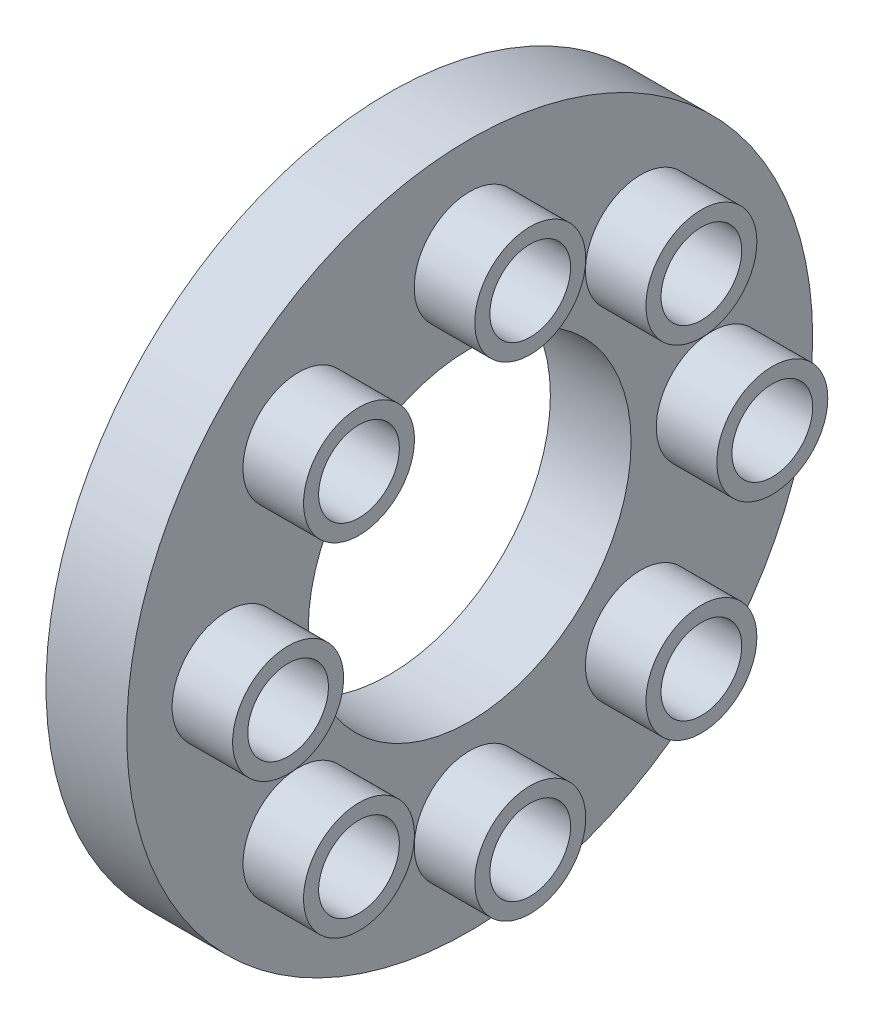
SolidWorks part; units mm, degrees
ref_plane "Front Plane" through (0, 0, 0) normal (0, 0, 1) x (1, 0, 0)
ref_plane "Top Plane" through (0, 0, 0) normal (0, 1, 0) x (1, 0, 0)
ref_plane "Right Plane" through (0, 0, 0) normal (1, 0, 0) x (0, 0, -1)
sketch "Sketch1" plane through (0, 0, 0) normal (1, 0, 0) x (0, 0, -1)
  line L0 (0, 0) -> (0, 12) construction
  circle A0 centre (0, 0) radius 17
  circle A1 centre (0, 12) radius 2
  circle A2 centre (8.4853, 8.4853) radius 2
  circle A3 centre (12, 0) radius 2
  circle A4 centre (8.4853, -8.4853) radius 2
  circle A5 centre (0, -12) radius 2
  circle A6 centre (-8.4853, -8.4853) radius 2
  circle A7 centre (-12, 0) radius 2
  circle A8 centre (-8.4853, 8.4853) radius 2
  circle A9 centre (0, 0) radius 8
  point P21 (0, 0)
  dimension "D1" = 34
  dimension "D3" = 4
  dimension "D5" = 16
  dimension "D2" = 12
  dimension "D4" = 8
extrude "Boss-Extrude1" add sketch "Sketch1" along normal blind 4
sketch "Sketch2" plane through (4, 0, 0) normal (1, 0, 0) x (0, 0, -1)
  circle A0 centre (8.4853, 8.4853) radius 2.75
  circle A1 centre (8.4853, 8.4853) radius 2
  circle A2 centre (12, 0) radius 2
  circle A3 centre (12, 0) radius 2.75
  circle A4 centre (8.4853, -8.4853) radius 2
  circle A5 centre (8.4853, -8.4853) radius 2.75
  circle A6 centre (0, -12) radius 2
  circle A7 centre (0, -12) radius 2.75
  circle A8 centre (-8.4853, -8.4853) radius 2
  circle A9 centre (-8.4853, -8.4853) radius 2.75
  circle A10 centre (-12, 0) radius 2
  circle A11 centre (-12, 0) radius 2.75
  circle A12 centre (-8.4853, 8.4853) radius 2
  circle A13 centre (-8.4853, 8.4853) radius 2.75
  circle A14 centre (0, 12) radius 2
  circle A15 centre (0, 12) radius 2.75
  point P27 (0, 0)
  dimension "D1" = 5.5
  dimension "D2" = 8
extrude "Boss-Extrude2" add sketch "Sketch2" along normal blind 3
